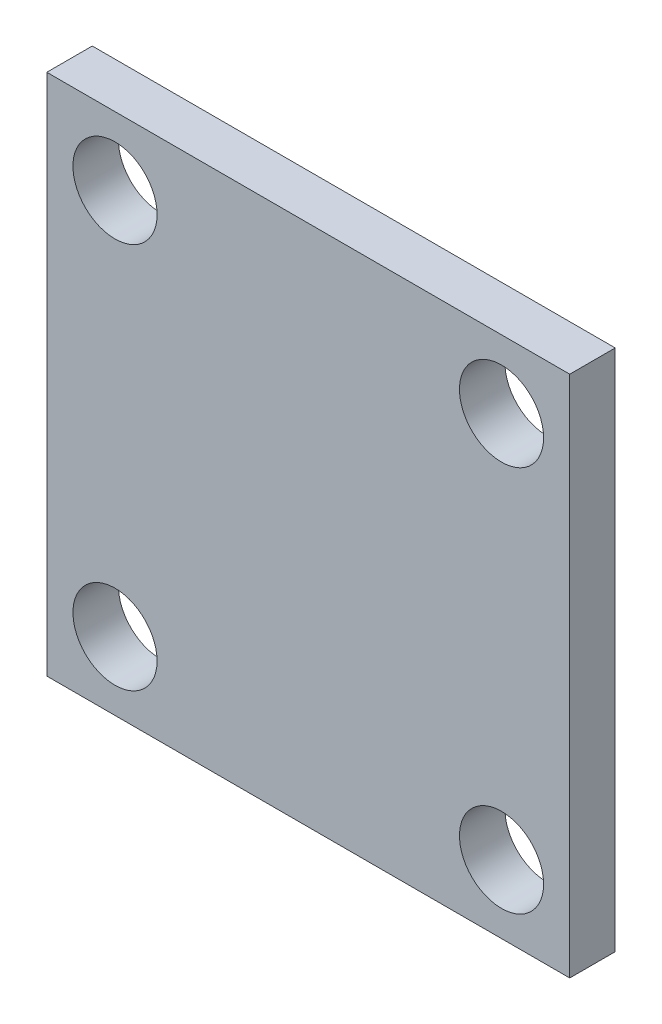
SolidWorks part; units mm, degrees
ref_plane "Front Plane" through (0, 0, 0) normal (0, 0, 1) x (1, 0, 0)
ref_plane "Top Plane" through (0, 0, 0) normal (0, 1, 0) x (1, 0, 0)
ref_plane "Right Plane" through (0, 0, 0) normal (1, 0, 0) x (0, 0, -1)
sketch "Sketch1" plane through (0, 0, 0) normal (0, 0, 1) x (1, 0, 0)
  line L1 (-11.5, -11.5) -> (11.5, -11.5)
  line L2 (-11.5, -11.5) -> (-11.5, 11.5)
  line L3 (-11.5, 11.5) -> (11.5, 11.5)
  line L4 (11.5, -11.5) -> (11.5, 11.5)
  line L5 (-11.5, -11.5) -> (11.5, 11.5) construction
  line L6 (-11.5, 11.5) -> (11.5, -11.5) construction
  line L7 (-8.5, -8.5) -> (8.5, -8.5) construction
  line L8 (-8.5, -8.5) -> (-8.5, 8.5) construction
  line L9 (-8.5, 8.5) -> (8.5, 8.5) construction
  line L10 (8.5, -8.5) -> (8.5, 8.5) construction
  line L11 (-8.5, -8.5) -> (8.5, 8.5) construction
  line L12 (-8.5, 8.5) -> (8.5, -8.5) construction
  circle A0 centre (-8.5, 8.5) radius 1.85
  circle A1 centre (8.5, 8.5) radius 1.85
  circle A2 centre (8.5, -8.5) radius 1.85
  circle A3 centre (-8.5, -8.5) radius 1.85
  point P0 (0, 0)
  point P6 (0, 0)
  dimension "D5" = 3.7
  dimension "D1" = 23
  dimension "D2" = 23
  dimension "D3" = 17
  dimension "D4" = 17
extrude "Boss-Extrude1" add sketch "Sketch1" along normal blind 2
